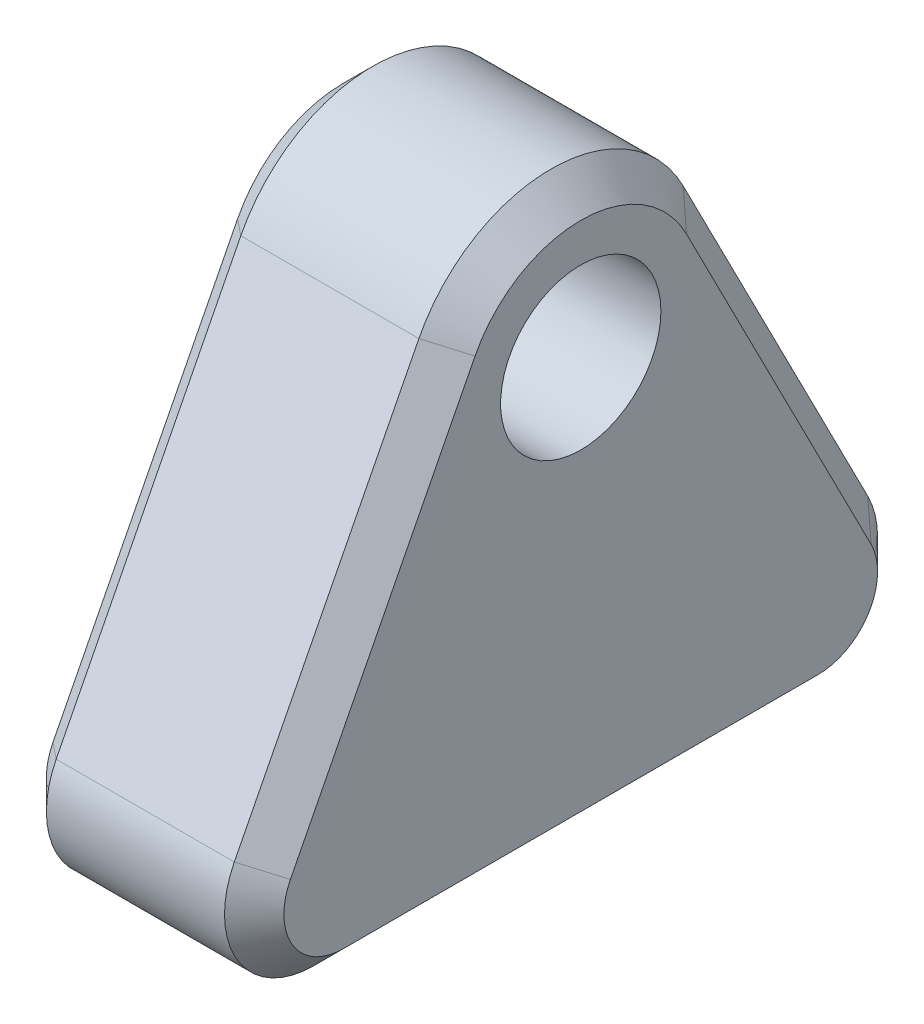
SolidWorks part; units mm, degrees
material "ABS PC"
ref_plane "Front" through (0, 0, 0) normal (0, 0, 1) x (1, 0, 0)
ref_plane "Top" through (0, 0, 0) normal (0, 1, 0) x (1, 0, 0)
ref_plane "Right" through (0, 0, 0) normal (1, 0, 0) x (0, 0, -1)
sketch "Sketch1" plane through (0, 0, 0) normal (1, 0, 0) x (0, 0, -1)
  line L0 (-4.4516, 2.2767) -> (-10.671, -9.884)
  line L1 (-8, -14.25) -> (8, -14.25)
  line L2 (10.671, -9.884) -> (4.4516, 2.2767)
  arc A0 (4.4516, 2.2767) -> (-4.4516, 2.2767) centre (0, 0) ccw
  arc A1 (10.671, -9.884) -> (8, -14.25) centre (8, -11.25) cw
  arc A2 (-8, -14.25) -> (-10.671, -9.884) centre (-8, -11.25) cw
  circle A3 centre (0, 0) radius 2.7
  dimension "D1" = 10
  dimension "D2" = 3
  dimension "D5" = 5.4
  dimension "D3" = 14.25
  dimension "D4" = 16
extrude "Boss-Extrude1" add sketch "Sketch1" along normal mid plane 8
chamfer "Chamfer1" distance 1 angle 45 12 edges at (-4, -12.8156, -10.5591) (-4, -3.8036, -7.5613) (-4, -14.25, 0) (-4, 5, 0) (-4, -12.8156, 10.5591) (-4, -3.8036, 7.5613) (4, -12.8156, -10.5591) (4, -3.8036, -7.5613) (4, -14.25, 0) (4, 5, 0) (4, -12.8156, 10.5591) (4, -3.8036, 7.5613)
sketch "Sketch3" plane through (0, -14.25, 0) normal (0, -1, 0) x (1, 0, 0)
  line L0 (0, -5) -> (0, 0) construction
  line L1 (0, 0) -> (0, 5) construction
  circle A0 centre (0, 5) radius 2.4
  circle A1 centre (0, -5) radius 2.4
  dimension "D2" = 4.8
  dimension "D3" = 10
extrude "Cut-Extrude1" cut sketch "Sketch3" against normal blind 7
chamfer "Chamfer2" distance 0.5 angle 45 2 edges at (0, -14.25, -7.4) (0, -14.25, 2.6)
